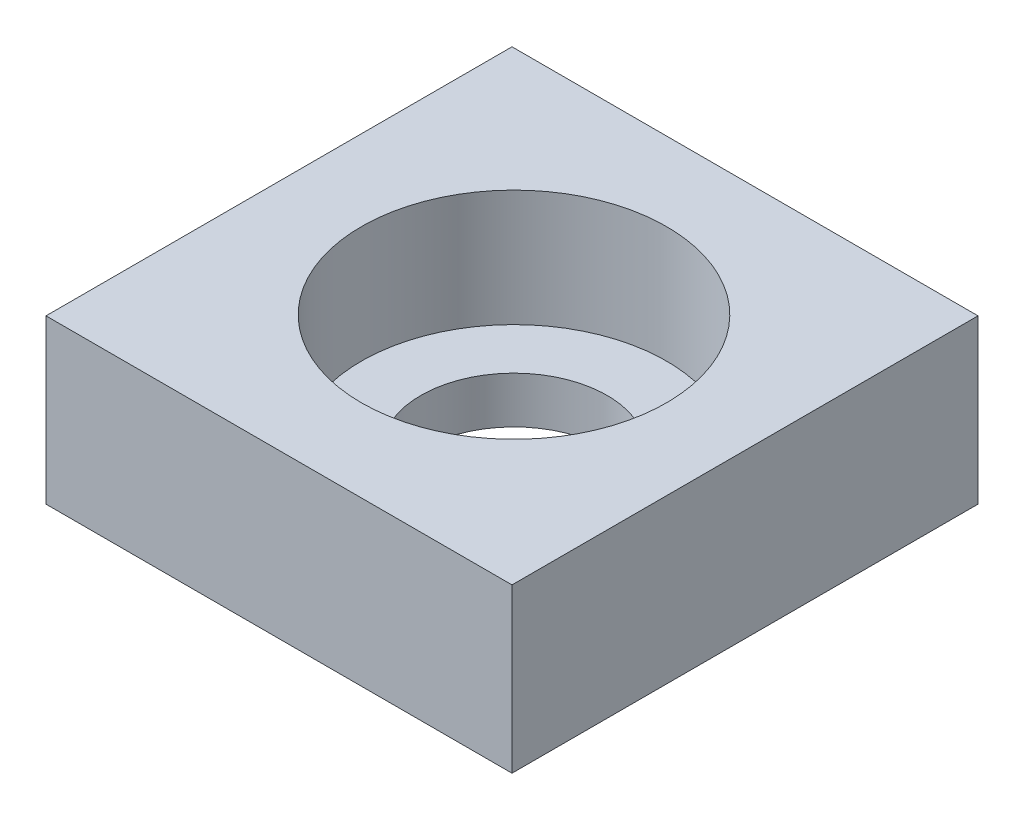
SolidWorks part; units mm, degrees
ref_plane "Front Plane" through (0, 0, 0) normal (0, 0, 1) x (1, 0, 0)
ref_plane "Top Plane" through (0, 0, 0) normal (0, 1, 0) x (1, 0, 0)
ref_plane "Right Plane" through (0, 0, 0) normal (1, 0, 0) x (0, 0, -1)
sketch "Sketch1" plane through (0, 0, 0) normal (0, 1, 0) x (1, 0, 0)
  line L1 (0, 0) -> (20, 0)
  line L2 (0, 0) -> (0, 20)
  line L3 (0, 20) -> (20, 20)
  line L4 (20, 0) -> (20, 20)
  dimension "D1" = 20
  dimension "D2" = 20
extrude "Boss-Extrude1" add sketch "Sketch1" along normal blind 7 contours L2 L3 L4 L1
sketch "Sketch2" plane through (0, 7, 0) normal (0, 1, 0) x (1, 0, 0)
  circle A0 centre (10, 10.0852) radius 6.55
  dimension "D1" = 13.1
extrude "Cut-Extrude1" cut sketch "Sketch2" against normal blind 5
sketch "Sketch3" plane through (0, 2, 0) normal (0, 1, 0) x (1, 0, 0)
  circle A0 centre (10, 10.0852) radius 4
  dimension "8" = 8
extrude "Cut-Extrude3" cut sketch "Sketch3" against normal up to surface (2 mm away) up to face at (10, 0, -10)
